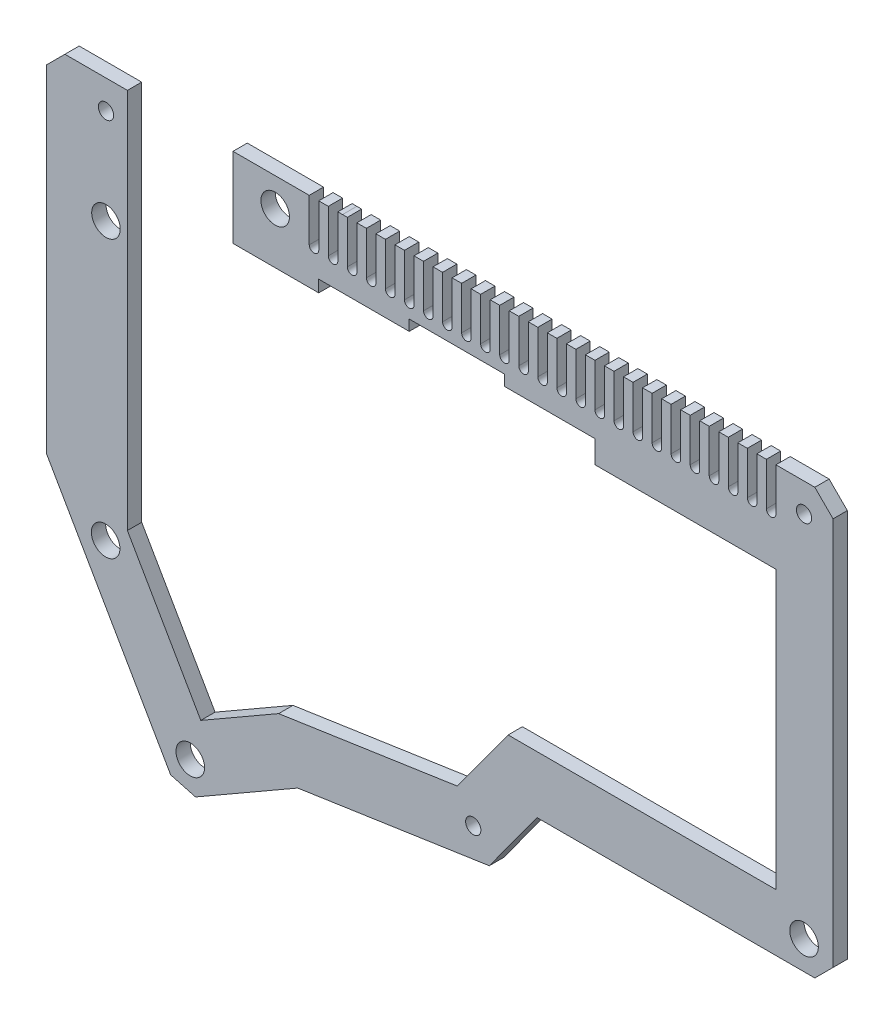
SolidWorks part; units mm, degrees
ref_plane "Plan de face" through (0, 0, 0) normal (0, 0, 1) x (1, 0, 0)
ref_plane "Plan de dessus" through (0, 0, 0) normal (0, 1, 0) x (1, 0, 0)
ref_plane "Plan de droite" through (0, 0, 0) normal (1, 0, 0) x (0, 0, -1)
sketch "Esquisse1" plane through (0, 0, 0) normal (0, 0, 1) x (1, 0, 0)
  line L0 (-117.3419, -15.4198) -> (-103.3409, -15.4198) construction
  line L1 (-103.3409, -15.4198) -> (-103.3409, -29.4208) construction
  line L2 (-103.3409, -29.4208) -> (-117.3419, -29.4208) construction
  line L3 (-117.3419, -29.4208) -> (-117.3419, -15.4198) construction
  line L4 (-98.3406, -27.0457) -> (-98.3406, -13.0447) construction
  line L5 (-98.3406, -13.0447) -> (-84.3396, -13.0447) construction
  line L6 (-84.3396, -13.0447) -> (-84.3396, -27.0457) construction
  line L7 (-84.3396, -27.0457) -> (-98.3406, -27.0457) construction
  line L8 (-79.3392, -24.6705) -> (-79.3392, -10.6695) construction
  line L9 (-79.3392, -10.6695) -> (-65.3382, -10.6695) construction
  line L10 (-65.3382, -10.6695) -> (-65.3382, -24.6705) construction
  line L11 (-65.3382, -24.6705) -> (-79.3392, -24.6705) construction
  line L12 (-60.3379, -27.0457) -> (-60.3379, -13.0447) construction
  line L13 (-60.3379, -13.0447) -> (-46.3369, -13.0447) construction
  line L14 (-46.3369, -13.0447) -> (-46.3369, -27.0457) construction
  line L15 (-46.3369, -27.0457) -> (-60.3379, -27.0457) construction
  line L16 (-41.3365, -31.796) -> (-41.3365, -17.795) construction
  line L17 (-41.3365, -17.795) -> (-27.3355, -17.795) construction
  line L18 (-27.3355, -17.795) -> (-27.3355, -31.796) construction
  line L19 (-27.3355, -31.796) -> (-41.3365, -31.796) construction
  line L20 (-22.3347, -31.796) -> (-22.3347, -17.795) construction
  line L21 (-22.3347, -17.795) -> (-8.3337, -17.795) construction
  line L22 (-8.3337, -17.795) -> (-8.3337, -31.796) construction
  line L23 (-8.3337, -31.796) -> (-22.3347, -31.796) construction
  line L24 (-117.3419, -34.4212) -> (-103.3409, -34.4212) construction
  line L25 (-103.3409, -34.4212) -> (-103.3409, -48.4222) construction
  line L26 (-103.3409, -48.4222) -> (-117.3419, -48.4222) construction
  line L27 (-117.3419, -48.4222) -> (-117.3419, -34.4212) construction
  line L28 (-98.3406, -32.046) -> (-84.3396, -32.046) construction
  line L29 (-84.3396, -32.046) -> (-84.3396, -46.047) construction
  line L30 (-84.3396, -46.047) -> (-98.3406, -46.047) construction
  line L31 (-98.3406, -46.047) -> (-98.3406, -32.046) construction
  line L32 (-79.3392, -29.6709) -> (-65.3382, -29.6709) construction
  line L33 (-65.3382, -29.6709) -> (-65.3382, -43.6718) construction
  line L34 (-65.3382, -43.6718) -> (-79.3392, -43.6718) construction
  line L35 (-79.3392, -43.6718) -> (-79.3392, -29.6709) construction
  line L36 (-60.3379, -32.046) -> (-46.3369, -32.046) construction
  line L37 (-46.3369, -32.046) -> (-46.3369, -46.047) construction
  line L38 (-46.3369, -46.047) -> (-60.3379, -46.047) construction
  line L39 (-60.3379, -46.047) -> (-60.3379, -32.046) construction
  line L40 (-41.3365, -36.7964) -> (-27.3355, -36.7964) construction
  line L41 (-27.3355, -36.7964) -> (-27.3355, -50.7973) construction
  line L42 (-27.3355, -50.7973) -> (-41.3365, -50.7973) construction
  line L43 (-41.3365, -50.7973) -> (-41.3365, -36.7964) construction
  line L44 (-22.3347, -36.7964) -> (-8.3337, -36.7964) construction
  line L45 (-8.3337, -36.7964) -> (-8.3337, -50.7973) construction
  line L46 (-8.3337, -50.7973) -> (-22.3347, -50.7973) construction
  line L47 (-22.3347, -50.7973) -> (-22.3347, -36.7964) construction
  line L48 (-22.3347, -55.7977) -> (-8.3337, -55.7977) construction
  line L49 (-8.3337, -55.7977) -> (-8.3337, -69.7987) construction
  line L50 (-8.3337, -69.7987) -> (-22.3347, -69.7987) construction
  line L51 (-22.3347, -69.7987) -> (-22.3347, -55.7977) construction
  line L52 (-41.3365, -55.7977) -> (-27.3355, -55.7977) construction
  line L53 (-27.3355, -55.7977) -> (-27.3355, -69.7987) construction
  line L54 (-27.3355, -69.7987) -> (-41.3365, -69.7987) construction
  line L55 (-41.3365, -69.7987) -> (-41.3365, -55.7977) construction
  line L56 (-60.3379, -51.0474) -> (-46.3369, -51.0474) construction
  line L57 (-46.3369, -51.0474) -> (-46.3369, -65.0484) construction
  line L58 (-46.3369, -65.0484) -> (-60.3379, -65.0484) construction
  line L59 (-60.3379, -65.0484) -> (-60.3379, -51.0474) construction
  line L60 (-79.3392, -48.6722) -> (-65.3382, -48.6722) construction
  line L61 (-65.3382, -48.6722) -> (-65.3382, -62.6732) construction
  line L62 (-65.3382, -62.6732) -> (-79.3392, -62.6732) construction
  line L63 (-79.3392, -62.6732) -> (-79.3392, -48.6722) construction
  line L64 (-98.3406, -51.0474) -> (-84.3396, -51.0474) construction
  line L65 (-84.3396, -51.0474) -> (-84.3396, -65.0484) construction
  line L66 (-84.3396, -65.0484) -> (-98.3406, -65.0484) construction
  line L67 (-98.3406, -65.0484) -> (-98.3406, -51.0474) construction
  line L68 (-117.3419, -53.4225) -> (-103.3409, -53.4225) construction
  line L69 (-103.3409, -53.4225) -> (-103.3409, -67.4235) construction
  line L70 (-103.3409, -67.4235) -> (-117.3419, -67.4235) construction
  line L71 (-117.3419, -67.4235) -> (-117.3419, -53.4225) construction
  line L72 (-88.8399, -70.6738) -> (-74.8389, -70.6738) construction
  line L73 (-74.8389, -70.6738) -> (-74.8389, -84.6747) construction
  line L74 (-74.8389, -84.6747) -> (-88.8399, -84.6747) construction
  line L75 (-88.8399, -84.6747) -> (-88.8399, -70.6738) construction
  line L76 (-111.4175, -75.4665) -> (-97.8899, -71.8565) construction
  line L77 (-97.8899, -71.8565) -> (-94.28, -85.3841) construction
  line L78 (-94.28, -85.3841) -> (-107.8075, -88.9941) construction
  line L79 (-107.8075, -88.9941) -> (-111.4175, -75.4665) construction
  line L80 (-134.6581, -81.5997) -> (-122.5281, -74.6075) construction
  line L81 (-122.5281, -74.6075) -> (-115.5359, -86.7375) construction
  line L82 (-115.5359, -86.7375) -> (-127.6659, -93.7297) construction
  line L83 (-127.6659, -93.7297) -> (-134.6581, -81.5997) construction
  line L86 (-6.3391, -71.9336) -> (-62.0853, -71.9336) construction
  line L89 (-72.824, -86.6446) -> (-62.0853, -71.9336) construction
  line L96 (-109.7697, -91.4639) -> (-73.0906, -86.6918) construction
  line L97 (-124.664, -99.8297) -> (-110.3971, -91.5881) construction
  line L98 (-139.9408, -76.5013) -> (-126.7151, -99.4281) construction
  line L99 (-119.8527, -15.5421) -> (-139.6028, -15.5421) construction
  line L100 (-100.8528, -13.2921) -> (-118.8527, -13.2921) construction
  line L101 (-63.8455, -8.5421) -> (-80.8528, -8.5421) construction
  line L102 (-44.8455, -10.792) -> (-62.8485, -10.792) construction
  line L103 (-25.8456, -15.5421) -> (-43.8486, -15.5421) construction
  line L104 (-6.8456, -15.5421) -> (-23.8529, -15.5421) construction
  line L105 (-6.2741, -71.3672) -> (-6.2741, -16.1136) construction
  line L106 (-23.8529, -71.9423) -> (-6.8456, -71.9423) construction
  line L107 (-61.8455, -71.9423) -> (-25.8456, -71.9423) construction
  line L108 (-72.6738, -86.4911) -> (-62.1363, -72.0583) construction
  line L109 (-140.1743, -16.1136) -> (-140.1743, -75.5958) construction
  line L110 (-134.3462, 1.5705) -> (-134.3466, -55.7217) construction
  line L111 (-134.3466, -55.7217) -> (-160.479, -70.8411) construction
  line L112 (-160.479, -70.8411) -> (-133.7613, -117.344) construction
  line L113 (-126.937, -119.1852) -> (-105.0783, -106.604) construction
  line L114 (-105.0783, -106.604) -> (-64.4097, -100.5586) construction
  line L115 (-64.4097, -100.5586) -> (-54.4636, -86.9336) construction
  line L116 (3.6609, -86.9336) -> (-54.4636, -86.9336) construction
  line L117 (8.6609, -81.9336) -> (8.6609, 1.315) construction
  line L122 (3.6609, 6.3153) -> (-96.3444, 6.3209) construction
  line L129 (8.6609, -86.9336) -> (8.6609, -0.6796) construction
  line L130 (-48.3431, 6.3182) -> (-96.3444, 6.3209) construction
  line L131 (-115.3458, 1.5705) -> (-134.3462, 1.5705) construction
  line L132 (-160.479, -3.4295) -> (-160.479, -70.8411) construction
  line L134 (-119.3463, 1.5705) -> (-119.3466, -64.3728) construction
  line L135 (-119.3466, -64.3728) -> (-135.695, -73.8315) construction
  line L136 (-140.0228, -71.3355) -> (-140.0228, 1.5705) construction
  line L138 (-160.479, -70.8411) -> (-131.2704, -121.6794) construction
  line L139 (-131.2704, -121.6794) -> (-105.0783, -106.604) construction
  line L140 (-133.7613, -117.344) -> (-126.937, -119.1852) construction
  line L142 (8.6609, 1.315) -> (3.6609, 6.3153) construction
  line L143 (8.6609, -86.9336) -> (-54.4636, -86.9336) construction
  line L144 (8.6609, -81.9336) -> (3.6609, -86.9336) construction
  line L147 (-103.3409, 6.3209) -> (-96.3444, 6.3209) construction
  line L148 (-103.3409, 6.3209) -> (-119.3463, 6.3209) construction
  line L149 (-119.3463, 6.3209) -> (-119.3463, 1.5705) construction
  line L150 (-140.0228, 1.5705) -> (-140.0228, 6.3209) construction
  line L151 (-140.0228, 6.3209) -> (-155.479, 6.3209) construction
  line L152 (-160.479, 1.3209) -> (-160.479, -3.4295) construction
  line L153 (-155.479, 6.3209) -> (-160.479, 1.3209) construction
  line L154 (8.6609, -1.685) -> (-119.3463, -1.6779) construction
  line L155 (-146.0924, -79.8227) -> (-128.3223, -110.752) construction
  line L156 (-128.3223, -110.752) -> (-107.7547, -98.9139) construction
  line L157 (-140.0228, -78.3428) -> (-126.1111, -102.5565)
  line L158 (-126.1111, -102.5565) -> (-109.762, -93.1464)
  line L159 (-109.762, -93.1464) -> (-72.2631, -87.5722)
  line L160 (-72.2631, -87.5722) -> (-61.5772, -72.9336)
  line L161 (-5.3391, -72.9336) -> (-61.5772, -72.9336)
  line L162 (-5.3391, -72.9336) -> (-5.3391, -14.6796)
  line L163 (-5.3391, -14.6796) -> (-43.3418, -14.6796)
  line L164 (-43.3418, -14.6796) -> (-43.3418, -9.9293)
  line L165 (-43.3418, -9.9293) -> (-62.3431, -9.9293)
  line L166 (-62.3431, -9.9293) -> (-62.3431, -7.681)
  line L167 (-62.3431, -7.681) -> (-82.3444, -7.6799)
  line L168 (-82.3444, -7.6799) -> (-82.3444, -9.9293)
  line L169 (-82.3444, -9.9293) -> (-101.3458, -9.9293)
  line L170 (-101.3458, -9.9293) -> (-101.3458, -12.4295)
  line L171 (-101.3458, -12.4295) -> (-119.3464, -12.4295)
  line L172 (-120.3463, -12.4295) -> (-120.3466, -64.3728) construction
  line L173 (-119.8474, -63.5072) -> (-140.5236, -75.4699) construction
  line L174 (-107.7547, -98.9139) -> (-68.8973, -93.1378) construction
  line L175 (-68.8973, -93.1378) -> (-58.5285, -78.9336) construction
  line L176 (0.6609, -78.9336) -> (-58.5285, -78.9336) construction
  line L177 (0.6609, -78.9336) -> (0.6609, -1.6845) construction
  line L178 (-62.3428, -1.681) -> (-82.3441, -1.6799) construction
  line L179 (0.6609, -78.9336) -> (0.6609, -14.6796) construction
  line L180 (-146.0228, -76.3355) -> (-146.0228, 1.5705) construction
  line L181 (-140.0228, -76.3355) -> (-140.0228, 1.5705) construction
  line L182 (-135.695, -73.8315) -> (-140.0228, -71.3355) construction
  line L183 (2.8324, 4.3153) -> (-96.3445, 4.3209)
  line L184 (-103.3409, 4.3209) -> (-96.3445, 4.3209)
  line L185 (-103.3409, 4.3209) -> (-119.3463, 4.3209)
  line L186 (-117.3463, 4.3209) -> (-117.3463, 1.5705) construction
  line L187 (-117.3463, 1.5705) -> (-117.3466, -65.5263) construction
  line L188 (-117.3466, -65.5263) -> (-135.6934, -76.1412) construction
  line L189 (-135.6934, -76.1412) -> (-142.0228, -72.4908) construction
  line L190 (-142.0228, -72.4908) -> (-142.0228, 1.5705) construction
  line L191 (-142.0228, 1.5705) -> (-142.0228, 4.3209) construction
  line L192 (-141.5228, 4.3209) -> (-154.6506, 4.3209)
  line L193 (-154.6506, 4.3209) -> (-158.479, 0.4924)
  line L194 (-158.479, 0.4924) -> (-158.479, -3.4295)
  line L195 (-158.479, -3.4295) -> (-158.479, -70.3075)
  line L196 (-158.479, -70.3075) -> (-132.44, -115.629)
  line L197 (-132.44, -115.629) -> (-127.2163, -117.0383)
  line L198 (-127.2163, -117.0383) -> (-105.7474, -104.6815)
  line L199 (-105.7474, -104.6815) -> (-65.5316, -98.7034)
  line L200 (-65.5316, -98.7034) -> (-55.4798, -84.9336)
  line L201 (2.8325, -84.9336) -> (-55.4798, -84.9336)
  line L202 (6.6609, -81.1052) -> (2.8325, -84.9336)
  line L203 (6.6609, -81.1052) -> (6.6609, 0.4866)
  line L204 (6.6609, 0.4866) -> (2.8324, 4.3153)
  line L205 (-103.3409, 4.3209) -> (-117.3463, 4.3209) construction
  line L206 (-142.0228, 4.3209) -> (-154.6506, 4.3209) construction
  line L207 (-140.0228, 4.3209) -> (-140.0228, -75.1802) construction
  line L208 (-119.3463, 4.3209) -> (-119.3464, -12.4295)
  line L209 (-140.0228, -78.3428) -> (-140.8899, -76.8336)
  line L210 (-101.3458, -12.4295) -> (-120.3463, -12.4295) construction
  line L211 (-140.8899, -76.8336) -> (-126.1111, -102.5565) construction
  line L217 (-6.3391, -71.9336) -> (-6.3391, -15.6796) construction
  line L220 (-6.3391, -15.6796) -> (-44.3418, -15.6796) construction
  line L221 (-44.3418, -15.6796) -> (-44.3418, -10.9293) construction
  line L222 (-44.3418, -10.9293) -> (-63.3431, -10.9293) construction
  line L223 (-63.3431, -10.9293) -> (-63.3431, -8.681) construction
  line L224 (-63.3431, -8.681) -> (-81.3444, -8.68) construction
  line L225 (-81.3444, -8.68) -> (-81.3444, -10.9293) construction
  line L226 (-81.3444, -10.9293) -> (-100.3458, -10.9293) construction
  line L227 (-100.3458, -10.9293) -> (-100.3458, -13.4295) construction
  line L228 (-100.3458, -13.4295) -> (-119.3463, -13.4295) construction
  line L231 (-119.3463, -13.4295) -> (-119.3466, -64.3728) construction
  line L232 (-119.3466, -64.3728) -> (-140.0228, -76.3355) construction
  line L233 (-140.0228, -76.3355) -> (-125.7426, -101.1906) construction
  line L234 (-125.7426, -101.1906) -> (-110.0965, -92.1851) construction
  line L235 (-110.0965, -92.1851) -> (-72.824, -86.6446) construction
  line L236 (-141.5228, -75.732) -> (-140.8899, -76.8336)
  line L238 (-141.5228, 4.3209) -> (-141.5228, -75.1802)
  line L239 (-141.5228, -75.1802) -> (-141.5228, -75.732)
  line L328 (-48.3431, 4.0707) -> (-48.3431, 6.3182) construction
  line L329 (-29.3418, 4.0707) -> (-48.3431, 4.0707) construction
  line L330 (-29.3418, -0.6796) -> (-29.3418, 4.0707) construction
  line L331 (8.6609, -0.6796) -> (-29.3418, -0.6796) construction
  line L332 (-115.3458, 4.0707) -> (-115.3458, 1.5705) construction
  line L333 (-96.3444, 4.0707) -> (-115.3458, 4.0707) construction
  line L334 (-96.3444, 6.3209) -> (-96.3444, 4.0707) construction
  circle A2 centre (0.6609, -1.6845) radius 1.6 construction
  circle A3 centre (0.6609, -1.6845) radius 3 construction
  circle A4 centre (-110.3971, -1.6784) radius 1.6 construction
  circle A5 centre (0.6609, -78.9336) radius 1.6 construction
  circle A6 centre (-68.8973, -93.1378) radius 1.6 construction
  circle A7 centre (-128.3223, -110.752) radius 1.6 construction
  circle A8 centre (-146.0924, -79.8227) radius 1.6 construction
  circle A9 centre (-146.0228, -1.6779) radius 1.6 construction
  point P138 (-160.479, 1.5705)
  point P139 (8.6609, 6.315)
  point P150 (-160.479, 6.3209)
  dimension "D3" = 3.2
  dimension "D4" = 6
  dimension "D6" = 3.2
  dimension "D7" = 3.2
  dimension "D8" = 3.2
  dimension "D9" = 3.2
  dimension "D10" = 3.2
  dimension "D15" = 3.2
  dimension "D2" = 6
  dimension "D1" = 15
  dimension "D5" = 1
  dimension "D13" = 6
  dimension "D16" = 2
  dimension "D17" = 1.5
extrude "Boss.-Extru.2" add sketch "Esquisse1" along normal blind 3
sketch "Esquisse2" plane through (0, 0, 3) normal (0, 0, 1) x (1, 0, 0)
  line L0 (6.6609, -3.0693) -> (-6.3391, -3.0693) construction
  line L1 (6.6609, -81.1052) -> (6.6609, 0.4866) construction
  line L2 (-6.3391, 4.3158) -> (-6.3391, -4.6842) construction
  line L3 (2.8324, 4.3153) -> (-96.3445, 4.3209) construction
  line L4 (-6.3391, 6.5821) -> (-6.3391, -4.6842) construction
  line L5 (-5.3391, 6.5821) -> (-5.3391, -4.6842)
  line L6 (-7.3391, 6.5821) -> (-7.3391, -4.6842)
  line L7 (-10.3391, 6.5821) -> (-10.3391, -4.6842) construction
  line L8 (-9.3391, 6.5821) -> (-9.3391, -4.6842)
  line L9 (-11.3391, 6.5821) -> (-11.3391, -4.6842)
  line L10 (-14.3391, 6.5821) -> (-14.3391, -4.6842) construction
  line L11 (-13.3391, 6.5821) -> (-13.3391, -4.6842)
  line L12 (-15.3391, 6.5821) -> (-15.3391, -4.6842)
  line L13 (-18.3391, 6.5821) -> (-18.3391, -4.6842) construction
  line L14 (-17.3391, 6.5821) -> (-17.3391, -4.6842)
  line L15 (-19.3391, 6.5821) -> (-19.3391, -4.6842)
  line L16 (-22.3391, 6.5821) -> (-22.3391, -4.6842) construction
  line L17 (-21.3391, 6.5821) -> (-21.3391, -4.6842)
  line L18 (-23.3391, 6.5821) -> (-23.3391, -4.6842)
  line L19 (-26.3391, 6.5821) -> (-26.3391, -4.6842) construction
  line L20 (-25.3391, 6.5821) -> (-25.3391, -4.6842)
  line L21 (-27.3391, 6.5821) -> (-27.3391, -4.6842)
  line L22 (-30.3391, 6.5821) -> (-30.3391, -4.6842) construction
  line L23 (-29.3391, 6.5821) -> (-29.3391, -4.6842)
  line L24 (-31.3391, 6.5821) -> (-31.3391, -4.6842)
  line L25 (-34.3391, 6.5821) -> (-34.3391, -4.6842) construction
  line L26 (-33.3391, 6.5821) -> (-33.3391, -4.6842)
  line L27 (-35.3391, 6.5821) -> (-35.3391, -4.6842)
  line L28 (-38.3391, 6.5821) -> (-38.3391, -4.6842) construction
  line L29 (-37.3391, 6.5821) -> (-37.3391, -4.6842)
  line L30 (-39.3391, 6.5821) -> (-39.3391, -4.6842)
  line L31 (-42.3391, 6.5821) -> (-42.3391, -4.6842) construction
  line L32 (-41.3391, 6.5821) -> (-41.3391, -4.6842)
  line L33 (-43.3391, 6.5821) -> (-43.3391, -4.6842)
  line L34 (-46.3391, 6.5821) -> (-46.3391, -4.6842) construction
  line L35 (-45.3391, 6.5821) -> (-45.3391, -4.6842)
  line L36 (-47.3391, 6.5821) -> (-47.3391, -4.6842)
  line L37 (-50.3391, 6.5821) -> (-50.3391, -4.6842) construction
  line L38 (-49.3391, 6.5821) -> (-49.3391, -4.6842)
  line L39 (-51.3391, 6.5821) -> (-51.3391, -4.6842)
  line L40 (-54.3391, 6.5821) -> (-54.3391, -4.6842) construction
  line L41 (-53.3391, 6.5821) -> (-53.3391, -4.6842)
  line L42 (-55.3391, 6.5821) -> (-55.3391, -4.6842)
  line L43 (-58.3391, 6.5821) -> (-58.3391, -4.6842) construction
  line L44 (-57.3391, 6.5821) -> (-57.3391, -4.6842)
  line L45 (-59.3391, 6.5821) -> (-59.3391, -4.6842)
  line L46 (-62.3391, 6.5821) -> (-62.3391, -4.6842) construction
  line L47 (-61.3391, 6.5821) -> (-61.3391, -4.6842)
  line L48 (-63.3391, 6.5821) -> (-63.3391, -4.6842)
  line L49 (-66.3391, 6.5821) -> (-66.3391, -4.6842) construction
  line L50 (-65.3391, 6.5821) -> (-65.3391, -4.6842)
  line L51 (-67.3391, 6.5821) -> (-67.3391, -4.6842)
  line L52 (-70.3391, 6.5821) -> (-70.3391, -4.6842) construction
  line L53 (-69.3391, 6.5821) -> (-69.3391, -4.6842)
  line L54 (-71.3391, 6.5821) -> (-71.3391, -4.6842)
  line L55 (-74.3391, 6.5821) -> (-74.3391, -4.6842) construction
  line L56 (-73.3391, 6.5821) -> (-73.3391, -4.6842)
  line L57 (-75.3391, 6.5821) -> (-75.3391, -4.6842)
  line L58 (-78.3391, 6.5821) -> (-78.3391, -4.6842) construction
  line L59 (-77.3391, 6.5821) -> (-77.3391, -4.6842)
  line L60 (-79.3391, 6.5821) -> (-79.3391, -4.6842)
  line L61 (-82.3391, 6.5821) -> (-82.3391, -4.6842) construction
  line L62 (-81.3391, 6.5821) -> (-81.3391, -4.6842)
  line L63 (-83.3391, 6.5821) -> (-83.3391, -4.6842)
  line L64 (-86.3391, 6.5821) -> (-86.3391, -4.6842) construction
  line L65 (-85.3391, 6.5821) -> (-85.3391, -4.6842)
  line L66 (-87.3391, 6.5821) -> (-87.3391, -4.6842)
  line L67 (-90.3391, 6.5821) -> (-90.3391, -4.6842) construction
  line L68 (-89.3391, 6.5821) -> (-89.3391, -4.6842)
  line L69 (-91.3391, 6.5821) -> (-91.3391, -4.6842)
  line L70 (-94.3391, 6.5821) -> (-94.3391, -4.6842) construction
  line L71 (-93.3391, 6.5821) -> (-93.3391, -4.6842)
  line L72 (-95.3391, 6.5821) -> (-95.3391, -4.6842)
  line L73 (-98.3391, 6.5821) -> (-98.3391, -4.6842) construction
  line L74 (-97.3391, 6.5821) -> (-97.3391, -4.6842)
  line L75 (-99.3391, 6.5821) -> (-99.3391, -4.6842)
  line L76 (-102.3391, 6.5821) -> (-102.3391, -4.6842) construction
  line L77 (-101.3391, 6.5821) -> (-101.3391, -4.6842)
  line L78 (-103.3391, 6.5821) -> (-103.3391, -4.6842)
  arc A0 (-5.3391, 6.5821) -> (-7.3391, 6.5821) centre (-6.3391, 6.5821) ccw
  arc A1 (-7.3391, -4.6842) -> (-5.3391, -4.6842) centre (-6.3391, -4.6842) ccw
  arc A2 (-9.3391, 6.5821) -> (-11.3391, 6.5821) centre (-10.3391, 6.5821) ccw
  arc A3 (-11.3391, -4.6842) -> (-9.3391, -4.6842) centre (-10.3391, -4.6842) ccw
  arc A4 (-13.3391, 6.5821) -> (-15.3391, 6.5821) centre (-14.3391, 6.5821) ccw
  arc A5 (-15.3391, -4.6842) -> (-13.3391, -4.6842) centre (-14.3391, -4.6842) ccw
  arc A6 (-17.3391, 6.5821) -> (-19.3391, 6.5821) centre (-18.3391, 6.5821) ccw
  arc A7 (-19.3391, -4.6842) -> (-17.3391, -4.6842) centre (-18.3391, -4.6842) ccw
  arc A8 (-21.3391, 6.5821) -> (-23.3391, 6.5821) centre (-22.3391, 6.5821) ccw
  arc A9 (-23.3391, -4.6842) -> (-21.3391, -4.6842) centre (-22.3391, -4.6842) ccw
  arc A10 (-25.3391, 6.5821) -> (-27.3391, 6.5821) centre (-26.3391, 6.5821) ccw
  arc A11 (-27.3391, -4.6842) -> (-25.3391, -4.6842) centre (-26.3391, -4.6842) ccw
  arc A12 (-29.3391, 6.5821) -> (-31.3391, 6.5821) centre (-30.3391, 6.5821) ccw
  arc A13 (-31.3391, -4.6842) -> (-29.3391, -4.6842) centre (-30.3391, -4.6842) ccw
  arc A14 (-33.3391, 6.5821) -> (-35.3391, 6.5821) centre (-34.3391, 6.5821) ccw
  arc A15 (-35.3391, -4.6842) -> (-33.3391, -4.6842) centre (-34.3391, -4.6842) ccw
  arc A16 (-37.3391, 6.5821) -> (-39.3391, 6.5821) centre (-38.3391, 6.5821) ccw
  arc A17 (-39.3391, -4.6842) -> (-37.3391, -4.6842) centre (-38.3391, -4.6842) ccw
  arc A18 (-41.3391, 6.5821) -> (-43.3391, 6.5821) centre (-42.3391, 6.5821) ccw
  arc A19 (-43.3391, -4.6842) -> (-41.3391, -4.6842) centre (-42.3391, -4.6842) ccw
  arc A20 (-45.3391, 6.5821) -> (-47.3391, 6.5821) centre (-46.3391, 6.5821) ccw
  arc A21 (-47.3391, -4.6842) -> (-45.3391, -4.6842) centre (-46.3391, -4.6842) ccw
  arc A22 (-49.3391, 6.5821) -> (-51.3391, 6.5821) centre (-50.3391, 6.5821) ccw
  arc A23 (-51.3391, -4.6842) -> (-49.3391, -4.6842) centre (-50.3391, -4.6842) ccw
  arc A24 (-53.3391, 6.5821) -> (-55.3391, 6.5821) centre (-54.3391, 6.5821) ccw
  arc A25 (-55.3391, -4.6842) -> (-53.3391, -4.6842) centre (-54.3391, -4.6842) ccw
  arc A26 (-57.3391, 6.5821) -> (-59.3391, 6.5821) centre (-58.3391, 6.5821) ccw
  arc A27 (-59.3391, -4.6842) -> (-57.3391, -4.6842) centre (-58.3391, -4.6842) ccw
  arc A28 (-61.3391, 6.5821) -> (-63.3391, 6.5821) centre (-62.3391, 6.5821) ccw
  arc A29 (-63.3391, -4.6842) -> (-61.3391, -4.6842) centre (-62.3391, -4.6842) ccw
  arc A30 (-65.3391, 6.5821) -> (-67.3391, 6.5821) centre (-66.3391, 6.5821) ccw
  arc A31 (-67.3391, -4.6842) -> (-65.3391, -4.6842) centre (-66.3391, -4.6842) ccw
  arc A32 (-69.3391, 6.5821) -> (-71.3391, 6.5821) centre (-70.3391, 6.5821) ccw
  arc A33 (-71.3391, -4.6842) -> (-69.3391, -4.6842) centre (-70.3391, -4.6842) ccw
  arc A34 (-73.3391, 6.5821) -> (-75.3391, 6.5821) centre (-74.3391, 6.5821) ccw
  arc A35 (-75.3391, -4.6842) -> (-73.3391, -4.6842) centre (-74.3391, -4.6842) ccw
  arc A36 (-77.3391, 6.5821) -> (-79.3391, 6.5821) centre (-78.3391, 6.5821) ccw
  arc A37 (-79.3391, -4.6842) -> (-77.3391, -4.6842) centre (-78.3391, -4.6842) ccw
  arc A38 (-81.3391, 6.5821) -> (-83.3391, 6.5821) centre (-82.3391, 6.5821) ccw
  arc A39 (-83.3391, -4.6842) -> (-81.3391, -4.6842) centre (-82.3391, -4.6842) ccw
  arc A40 (-85.3391, 6.5821) -> (-87.3391, 6.5821) centre (-86.3391, 6.5821) ccw
  arc A41 (-87.3391, -4.6842) -> (-85.3391, -4.6842) centre (-86.3391, -4.6842) ccw
  arc A42 (-89.3391, 6.5821) -> (-91.3391, 6.5821) centre (-90.3391, 6.5821) ccw
  arc A43 (-91.3391, -4.6842) -> (-89.3391, -4.6842) centre (-90.3391, -4.6842) ccw
  arc A44 (-93.3391, 6.5821) -> (-95.3391, 6.5821) centre (-94.3391, 6.5821) ccw
  arc A45 (-95.3391, -4.6842) -> (-93.3391, -4.6842) centre (-94.3391, -4.6842) ccw
  arc A46 (-97.3391, 6.5821) -> (-99.3391, 6.5821) centre (-98.3391, 6.5821) ccw
  arc A47 (-99.3391, -4.6842) -> (-97.3391, -4.6842) centre (-98.3391, -4.6842) ccw
  arc A48 (-101.3391, 6.5821) -> (-103.3391, 6.5821) centre (-102.3391, 6.5821) ccw
  arc A49 (-103.3391, -4.6842) -> (-101.3391, -4.6842) centre (-102.3391, -4.6842) ccw
  point P9 (-6.3391, 0.949)
  point P17 (-10.3391, 0.949)
  point P24 (-14.3391, 0.949)
  point P31 (-18.3391, 0.949)
  point P38 (-22.3391, 0.949)
  point P45 (-26.3391, 0.949)
  point P52 (-30.3391, 0.949)
  point P59 (-34.3391, 0.949)
  point P66 (-38.3391, 0.949)
  point P73 (-42.3391, 0.949)
  point P80 (-46.3391, 0.949)
  point P87 (-50.3391, 0.949)
  point P94 (-54.3391, 0.949)
  point P101 (-58.3391, 0.949)
  point P108 (-62.3391, 0.949)
  point P115 (-66.3391, 0.949)
  point P122 (-70.3391, 0.949)
  point P129 (-74.3391, 0.949)
  point P136 (-78.3391, 0.949)
  point P143 (-82.3391, 0.949)
  point P150 (-86.3391, 0.949)
  point P157 (-90.3391, 0.949)
  point P164 (-94.3391, 0.949)
  point P171 (-98.3391, 0.949)
  point P178 (-102.3391, 0.949)
  dimension "D3" = 25
  dimension "D1" = 13
  dimension "D2" = 9
extrude "Enlèv. mat.-Extru.1" cut sketch "Esquisse2" against normal blind 3
sketch "Esquisse3" plane through (0, 0, 0) normal (0, 0, 1) x (1, 0, 0)
  line L96 (-146.0228, -1.6779) -> (-146.0228, -21.6779) construction
  circle A3 centre (0.5703, -1.6845) radius 3 construction
  circle A10 centre (-110.4876, -1.6784) radius 3
  circle A11 centre (-146.0228, -1.6779) radius 3 construction
  circle A12 centre (-146.0924, -79.8227) radius 3
  circle A13 centre (-128.3223, -110.752) radius 3
  circle A14 centre (-68.8973, -93.1378) radius 3 construction
  circle A15 centre (0.5703, -78.9336) radius 3
  circle A16 centre (-68.8973, -93.1378) radius 1.6
  circle A17 centre (-146.0228, -1.6779) radius 1.6
  circle A18 centre (0.5703, -1.6845) radius 1.6
  circle A19 centre (-146.0228, -21.6779) radius 3
  point P89 (-119.3466, -64.3728)
  point P133 (-96.435, 6.3209)
  point P137 (-119.3463, 1.5705)
  point P145 (3.5703, 6.3153)
  point P152 (-119.3463, 6.3209)
  point P158 (-140.8899, -76.8336)
  point P161 (-126.1111, -102.5565)
  point P174 (-101.3458, -12.4295)
  point P175 (-120.3463, -12.4295)
  point P199 (3.1561, 5.3153)
  point P200 (-96.435, 5.3209)
  point P201 (-103.4315, 5.3209)
  dimension "D3" = 3.2
  dimension "D4" = 6
  dimension "D1" = 3.2
  dimension "D2" = 3.2
extrude "Enlèv. mat.-Extru.3" cut sketch "Esquisse3" along normal blind 10
sketch "Esquisse4" plane through (0, 0, 3) normal (0, 0, 1) x (1, 0, 0)
  line L106 (2.8324, 4.3153) -> (-5.3391, 4.3158)
  line L107 (-5.3391, 4.3158) -> (-5.3391, -4.6842)
  line L108 (-7.3391, -4.6842) -> (-7.3391, 4.3159)
  line L109 (-7.3391, 4.3159) -> (-9.3391, 4.316)
  line L110 (-9.3391, 4.316) -> (-9.3391, -4.6842)
  line L111 (-11.3391, -4.6842) -> (-11.3391, 4.3161)
  line L112 (-11.3391, 4.3161) -> (-13.3391, 4.3162)
  line L113 (-13.3391, 4.3162) -> (-13.3391, -4.6842)
  line L114 (-15.3391, -4.6842) -> (-15.3391, 4.3163)
  line L115 (-15.3391, 4.3163) -> (-17.3391, 4.3165)
  line L116 (-17.3391, 4.3165) -> (-17.3391, -4.6842)
  line L117 (-19.3391, -4.6842) -> (-19.3391, 4.3166)
  line L118 (-19.3391, 4.3166) -> (-21.3391, 4.3167)
  line L119 (-21.3391, 4.3167) -> (-21.3391, -4.6842)
  line L120 (-23.3391, -4.6842) -> (-23.3391, 4.3168)
  line L121 (-23.3391, 4.3168) -> (-25.3391, 4.3169)
  line L122 (-25.3391, 4.3169) -> (-25.3391, -4.6842)
  line L123 (-27.3391, -4.6842) -> (-27.3391, 4.317)
  line L124 (-27.3391, 4.317) -> (-29.3391, 4.3171)
  line L125 (-29.3391, 4.3171) -> (-29.3391, -4.6842)
  line L126 (-31.3391, -4.6842) -> (-31.3391, 4.3172)
  line L127 (-31.3391, 4.3172) -> (-33.3391, 4.3173)
  line L128 (-33.3391, 4.3173) -> (-33.3391, -4.6842)
  line L129 (-35.3391, -4.6842) -> (-35.3391, 4.3175)
  line L130 (-35.3391, 4.3175) -> (-37.3391, 4.3176)
  line L131 (-37.3391, 4.3176) -> (-37.3391, -4.6842)
  line L132 (-39.3391, -4.6842) -> (-39.3391, 4.3177)
  line L133 (-39.3391, 4.3177) -> (-41.3391, 4.3178)
  line L134 (-41.3391, 4.3178) -> (-41.3391, -4.6842)
  line L135 (-43.3391, -4.6842) -> (-43.3391, 4.3179)
  line L136 (-43.3391, 4.3179) -> (-45.3391, 4.318)
  line L137 (-45.3391, 4.318) -> (-45.3391, -4.6842)
  line L138 (-47.3391, -4.6842) -> (-47.3391, 4.3181)
  line L139 (-47.3391, 4.3181) -> (-49.3391, 4.3182)
  line L140 (-49.3391, 4.3182) -> (-49.3391, -4.6842)
  line L141 (-51.3391, -4.6842) -> (-51.3391, 4.3183)
  line L142 (-51.3391, 4.3183) -> (-53.3391, 4.3185)
  line L143 (-53.3391, 4.3185) -> (-53.3391, -4.6842)
  line L144 (-55.3391, -4.6842) -> (-55.3391, 4.3186)
  line L145 (-55.3391, 4.3186) -> (-57.3391, 4.3187)
  line L146 (-57.3391, 4.3187) -> (-57.3391, -4.6842)
  line L147 (-59.3391, -4.6842) -> (-59.3391, 4.3188)
  line L148 (-59.3391, 4.3188) -> (-61.3391, 4.3189)
  line L149 (-61.3391, 4.3189) -> (-61.3391, -4.6842)
  line L150 (-63.3391, -4.6842) -> (-63.3391, 4.319)
  line L151 (-63.3391, 4.319) -> (-65.3391, 4.3191)
  line L152 (-65.3391, 4.3191) -> (-65.3391, -4.6842)
  line L153 (-67.3391, -4.6842) -> (-67.3391, 4.3192)
  line L154 (-67.3391, 4.3192) -> (-69.3391, 4.3194)
  line L155 (-69.3391, 4.3194) -> (-69.3391, -4.6842)
  line L156 (-71.3391, -4.6842) -> (-71.3391, 4.3195)
  line L157 (-71.3391, 4.3195) -> (-73.3391, 4.3196)
  line L158 (-73.3391, 4.3196) -> (-73.3391, -4.6842)
  line L159 (-75.3391, -4.6842) -> (-75.3391, 4.3197)
  line L160 (-75.3391, 4.3197) -> (-77.3391, 4.3198)
  line L161 (-77.3391, 4.3198) -> (-77.3391, -4.6842)
  line L162 (-79.3391, -4.6842) -> (-79.3391, 4.3199)
  line L163 (-79.3391, 4.3199) -> (-81.3391, 4.32)
  line L164 (-81.3391, 4.32) -> (-81.3391, -4.6842)
  line L165 (-83.3391, -4.6842) -> (-83.3391, 4.3201)
  line L166 (-83.3391, 4.3201) -> (-85.3391, 4.3202)
  line L167 (-85.3391, 4.3202) -> (-85.3391, -4.6842)
  line L168 (-87.3391, -4.6842) -> (-87.3391, 4.3204)
  line L169 (-87.3391, 4.3204) -> (-89.3391, 4.3205)
  line L170 (-89.3391, 4.3205) -> (-89.3391, -4.6842)
  line L171 (-91.3391, -4.6842) -> (-91.3391, 4.3206)
  line L172 (-91.3391, 4.3206) -> (-93.3391, 4.3207)
  line L173 (-93.3391, 4.3207) -> (-93.3391, -4.6842)
  line L174 (-95.3391, -4.6842) -> (-95.3391, 4.3208)
  line L175 (-95.3391, 4.3208) -> (-96.3445, 4.3209)
  line L176 (-96.3445, 4.3209) -> (-97.3391, 4.3209)
  line L177 (-97.3391, 4.3209) -> (-97.3391, -4.6842)
  line L178 (-99.3391, -4.6842) -> (-99.3391, 4.3209)
  line L179 (-99.3391, 4.3209) -> (-101.3391, 4.3209)
  line L180 (-101.3391, 4.3209) -> (-101.3391, -4.6842)
  line L181 (-103.3391, -4.6842) -> (-103.3391, 4.3209)
  line L182 (-103.3391, 4.3209) -> (-119.3463, 4.3209)
  line L183 (-119.3463, 4.3209) -> (-119.3464, -12.4295)
  line L184 (-119.3464, -12.4295) -> (-101.3458, -12.4295)
  line L185 (-101.3458, -12.4295) -> (-101.3458, -9.9293)
  line L186 (-101.3458, -9.9293) -> (-82.3444, -9.9293)
  line L187 (-82.3444, -9.9293) -> (-82.3444, -7.6799)
  line L188 (-82.3444, -7.6799) -> (-62.3431, -7.681)
  line L189 (-62.3431, -7.681) -> (-62.3431, -9.9293)
  line L190 (-62.3431, -9.9293) -> (-43.3418, -9.9293)
  line L191 (-43.3418, -9.9293) -> (-43.3418, -14.6796)
  line L192 (-43.3418, -14.6796) -> (-5.3391, -14.6796)
  line L193 (-5.3391, -14.6796) -> (-5.3391, -72.9336)
  line L194 (-5.3391, -72.9336) -> (-61.5772, -72.9336)
  line L195 (-61.5772, -72.9336) -> (-72.2631, -87.5722)
  line L196 (-72.2631, -87.5722) -> (-109.762, -93.1464)
  line L197 (-109.762, -93.1464) -> (-126.1111, -102.5565)
  line L198 (-126.1111, -102.5565) -> (-141.5228, -75.732)
  line L199 (-141.5228, -75.732) -> (-141.5228, 4.3209)
  line L200 (-141.5228, 4.3209) -> (-154.6506, 4.3209)
  line L201 (-154.6506, 4.3209) -> (-158.479, 0.4924)
  line L202 (-158.479, 0.4924) -> (-158.479, -70.3075)
  line L203 (-158.479, -70.3075) -> (-132.44, -115.629)
  line L204 (-132.44, -115.629) -> (-127.2163, -117.0383)
  line L205 (-127.2163, -117.0383) -> (-105.7474, -104.6815)
  line L206 (-105.7474, -104.6815) -> (-65.5316, -98.7034)
  line L207 (-65.5316, -98.7034) -> (-55.4798, -84.9336)
  line L208 (-55.4798, -84.9336) -> (2.8325, -84.9336)
  line L209 (2.8325, -84.9336) -> (6.6609, -81.1052)
  line L210 (6.6609, -81.1052) -> (6.6609, 0.4866)
  line L211 (6.6609, 0.4866) -> (2.8324, 4.3153)
  line L212 (2.8324, 4.3153) -> (-5.3391, 4.3158)
  line L213 (-5.3391, 4.3158) -> (-5.3391, -4.6842)
  line L214 (-7.3391, -4.6842) -> (-7.3391, 4.3159)
  line L215 (-7.3391, 4.3159) -> (-9.3391, 4.316)
  line L216 (-9.3391, 4.316) -> (-9.3391, -4.6842)
  line L217 (-11.3391, -4.6842) -> (-11.3391, 4.3161)
  line L218 (-11.3391, 4.3161) -> (-13.3391, 4.3162)
  line L219 (-13.3391, 4.3162) -> (-13.3391, -4.6842)
  line L220 (-15.3391, -4.6842) -> (-15.3391, 4.3163)
  line L221 (-15.3391, 4.3163) -> (-17.3391, 4.3165)
  line L222 (-17.3391, 4.3165) -> (-17.3391, -4.6842)
  line L223 (-19.3391, -4.6842) -> (-19.3391, 4.3166)
  line L224 (-19.3391, 4.3166) -> (-21.3391, 4.3167)
  line L225 (-21.3391, 4.3167) -> (-21.3391, -4.6842)
  line L226 (-23.3391, -4.6842) -> (-23.3391, 4.3168)
  line L227 (-23.3391, 4.3168) -> (-25.3391, 4.3169)
  line L228 (-25.3391, 4.3169) -> (-25.3391, -4.6842)
  line L229 (-27.3391, -4.6842) -> (-27.3391, 4.317)
  line L230 (-27.3391, 4.317) -> (-29.3391, 4.3171)
  line L231 (-29.3391, 4.3171) -> (-29.3391, -4.6842)
  line L232 (-31.3391, -4.6842) -> (-31.3391, 4.3172)
  line L233 (-31.3391, 4.3172) -> (-33.3391, 4.3173)
  line L234 (-33.3391, 4.3173) -> (-33.3391, -4.6842)
  line L235 (-35.3391, -4.6842) -> (-35.3391, 4.3175)
  line L236 (-35.3391, 4.3175) -> (-37.3391, 4.3176)
  line L237 (-37.3391, 4.3176) -> (-37.3391, -4.6842)
  line L238 (-39.3391, -4.6842) -> (-39.3391, 4.3177)
  line L239 (-39.3391, 4.3177) -> (-41.3391, 4.3178)
  line L240 (-41.3391, 4.3178) -> (-41.3391, -4.6842)
  line L241 (-43.3391, -4.6842) -> (-43.3391, 4.3179)
  line L242 (-43.3391, 4.3179) -> (-45.3391, 4.318)
  line L243 (-45.3391, 4.318) -> (-45.3391, -4.6842)
  line L244 (-47.3391, -4.6842) -> (-47.3391, 4.3181)
  line L245 (-47.3391, 4.3181) -> (-49.3391, 4.3182)
  line L246 (-49.3391, 4.3182) -> (-49.3391, -4.6842)
  line L247 (-51.3391, -4.6842) -> (-51.3391, 4.3183)
  line L248 (-51.3391, 4.3183) -> (-53.3391, 4.3185)
  line L249 (-53.3391, 4.3185) -> (-53.3391, -4.6842)
  line L250 (-55.3391, -4.6842) -> (-55.3391, 4.3186)
  line L251 (-55.3391, 4.3186) -> (-57.3391, 4.3187)
  line L252 (-57.3391, 4.3187) -> (-57.3391, -4.6842)
  line L253 (-59.3391, -4.6842) -> (-59.3391, 4.3188)
  line L254 (-59.3391, 4.3188) -> (-61.3391, 4.3189)
  line L255 (-61.3391, 4.3189) -> (-61.3391, -4.6842)
  line L256 (-63.3391, -4.6842) -> (-63.3391, 4.319)
  line L257 (-63.3391, 4.319) -> (-65.3391, 4.3191)
  line L258 (-65.3391, 4.3191) -> (-65.3391, -4.6842)
  line L259 (-67.3391, -4.6842) -> (-67.3391, 4.3192)
  line L260 (-67.3391, 4.3192) -> (-69.3391, 4.3194)
  line L261 (-69.3391, 4.3194) -> (-69.3391, -4.6842)
  line L262 (-71.3391, -4.6842) -> (-71.3391, 4.3195)
  line L263 (-71.3391, 4.3195) -> (-73.3391, 4.3196)
  line L264 (-73.3391, 4.3196) -> (-73.3391, -4.6842)
  line L265 (-75.3391, -4.6842) -> (-75.3391, 4.3197)
  line L266 (-75.3391, 4.3197) -> (-77.3391, 4.3198)
  line L267 (-77.3391, 4.3198) -> (-77.3391, -4.6842)
  line L268 (-79.3391, -4.6842) -> (-79.3391, 4.3199)
  line L269 (-79.3391, 4.3199) -> (-81.3391, 4.32)
  line L270 (-81.3391, 4.32) -> (-81.3391, -4.6842)
  line L271 (-83.3391, -4.6842) -> (-83.3391, 4.3201)
  line L272 (-83.3391, 4.3201) -> (-85.3391, 4.3202)
  line L273 (-85.3391, 4.3202) -> (-85.3391, -4.6842)
  line L274 (-87.3391, -4.6842) -> (-87.3391, 4.3204)
  line L275 (-87.3391, 4.3204) -> (-89.3391, 4.3205)
  line L276 (-89.3391, 4.3205) -> (-89.3391, -4.6842)
  line L277 (-91.3391, -4.6842) -> (-91.3391, 4.3206)
  line L278 (-91.3391, 4.3206) -> (-93.3391, 4.3207)
  line L279 (-93.3391, 4.3207) -> (-93.3391, -4.6842)
  line L280 (-95.3391, -4.6842) -> (-95.3391, 4.3208)
  line L281 (-95.3391, 4.3208) -> (-96.3445, 4.3209)
  line L282 (-96.3445, 4.3209) -> (-97.3391, 4.3209)
  line L283 (-97.3391, 4.3209) -> (-97.3391, -4.6842)
  line L284 (-99.3391, -4.6842) -> (-99.3391, 4.3209)
  line L285 (-99.3391, 4.3209) -> (-101.3391, 4.3209)
  line L286 (-101.3391, 4.3209) -> (-101.3391, -4.6842)
  line L287 (-103.3391, -4.6842) -> (-103.3391, 4.3209)
  line L288 (-103.3391, 4.3209) -> (-119.3463, 4.3209)
  line L289 (-119.3463, 4.3209) -> (-119.3464, -12.4295)
  line L290 (-119.3464, -12.4295) -> (-101.3458, -12.4295)
  line L291 (-101.3458, -12.4295) -> (-101.3458, -9.9293)
  line L292 (-101.3458, -9.9293) -> (-82.3444, -9.9293)
  line L293 (-82.3444, -9.9293) -> (-82.3444, -7.6799)
  line L294 (-82.3444, -7.6799) -> (-62.3431, -7.681)
  line L295 (-62.3431, -7.681) -> (-62.3431, -9.9293)
  line L296 (-62.3431, -9.9293) -> (-43.3418, -9.9293)
  line L297 (-43.3418, -9.9293) -> (-43.3418, -14.6796)
  line L298 (-43.3418, -14.6796) -> (-5.3391, -14.6796)
  line L299 (-5.3391, -14.6796) -> (-5.3391, -72.9336)
  line L300 (-5.3391, -72.9336) -> (-61.5772, -72.9336)
  line L301 (-61.5772, -72.9336) -> (-72.2631, -87.5722)
  line L302 (-72.2631, -87.5722) -> (-109.762, -93.1464)
  line L303 (-109.762, -93.1464) -> (-126.1111, -102.5565)
  line L304 (-126.1111, -102.5565) -> (-141.5228, -75.732)
  line L305 (-141.5228, -75.732) -> (-141.5228, 4.3209)
  line L306 (-141.5228, 4.3209) -> (-154.6506, 4.3209)
  line L307 (-154.6506, 4.3209) -> (-158.479, 0.4924)
  line L308 (-158.479, 0.4924) -> (-158.479, -70.3075)
  line L309 (-158.479, -70.3075) -> (-132.44, -115.629)
  line L310 (-132.44, -115.629) -> (-127.2163, -117.0383)
  line L311 (-127.2163, -117.0383) -> (-105.7474, -104.6815)
  line L312 (-105.7474, -104.6815) -> (-65.5316, -98.7034)
  line L313 (-65.5316, -98.7034) -> (-55.4798, -84.9336)
  line L314 (-55.4798, -84.9336) -> (2.8325, -84.9336)
  line L315 (2.8325, -84.9336) -> (6.6609, -81.1052)
  line L316 (6.6609, -81.1052) -> (6.6609, 0.4866)
  line L317 (6.6609, 0.4866) -> (2.8324, 4.3153)
  circle A0 centre (-146.0228, -1.6779) radius 1.6 construction
  circle A1 centre (-146.0228, -21.6779) radius 3 construction
  circle A2 centre (-146.0924, -79.8227) radius 3 construction
  circle A3 centre (-128.3223, -110.752) radius 3 construction
  circle A4 centre (-68.8973, -93.1378) radius 1.6 construction
  circle A5 centre (-110.4876, -1.6784) radius 3 construction
  circle A6 centre (0.5703, -1.6845) radius 1.6 construction
  circle A7 centre (0.5703, -78.9336) radius 3 construction
  circle A8 centre (-146.0228, -1.6779) radius 1.6
  circle A9 centre (-146.0228, -21.6779) radius 3
  circle A10 centre (-146.0924, -79.8227) radius 3
  circle A11 centre (-128.3223, -110.752) radius 3
  circle A12 centre (-68.8973, -93.1378) radius 1.6
  circle A13 centre (-110.4876, -1.6784) radius 3
  circle A14 centre (0.5703, -1.6845) radius 1.6
  circle A15 centre (0.5703, -78.9336) radius 3
  arc A25 (-7.3391, -4.6842) -> (-5.3391, -4.6842) centre (-6.3391, -4.6842) ccw
  arc A26 (-11.3391, -4.6842) -> (-9.3391, -4.6842) centre (-10.3391, -4.6842) ccw
  arc A27 (-15.3391, -4.6842) -> (-13.3391, -4.6842) centre (-14.3391, -4.6842) ccw
  arc A28 (-19.3391, -4.6842) -> (-17.3391, -4.6842) centre (-18.3391, -4.6842) ccw
  arc A29 (-23.3391, -4.6842) -> (-21.3391, -4.6842) centre (-22.3391, -4.6842) ccw
  arc A30 (-27.3391, -4.6842) -> (-25.3391, -4.6842) centre (-26.3391, -4.6842) ccw
  arc A31 (-31.3391, -4.6842) -> (-29.3391, -4.6842) centre (-30.3391, -4.6842) ccw
  arc A32 (-35.3391, -4.6842) -> (-33.3391, -4.6842) centre (-34.3391, -4.6842) ccw
  arc A33 (-39.3391, -4.6842) -> (-37.3391, -4.6842) centre (-38.3391, -4.6842) ccw
  arc A34 (-43.3391, -4.6842) -> (-41.3391, -4.6842) centre (-42.3391, -4.6842) ccw
  arc A35 (-47.3391, -4.6842) -> (-45.3391, -4.6842) centre (-46.3391, -4.6842) ccw
  arc A36 (-51.3391, -4.6842) -> (-49.3391, -4.6842) centre (-50.3391, -4.6842) ccw
  arc A37 (-55.3391, -4.6842) -> (-53.3391, -4.6842) centre (-54.3391, -4.6842) ccw
  arc A38 (-59.3391, -4.6842) -> (-57.3391, -4.6842) centre (-58.3391, -4.6842) ccw
  arc A39 (-63.3391, -4.6842) -> (-61.3391, -4.6842) centre (-62.3391, -4.6842) ccw
  arc A40 (-67.3391, -4.6842) -> (-65.3391, -4.6842) centre (-66.3391, -4.6842) ccw
  arc A41 (-71.3391, -4.6842) -> (-69.3391, -4.6842) centre (-70.3391, -4.6842) ccw
  arc A42 (-75.3391, -4.6842) -> (-73.3391, -4.6842) centre (-74.3391, -4.6842) ccw
  arc A43 (-79.3391, -4.6842) -> (-77.3391, -4.6842) centre (-78.3391, -4.6842) ccw
  arc A44 (-83.3391, -4.6842) -> (-81.3391, -4.6842) centre (-82.3391, -4.6842) ccw
  arc A45 (-87.3391, -4.6842) -> (-85.3391, -4.6842) centre (-86.3391, -4.6842) ccw
  arc A46 (-91.3391, -4.6842) -> (-89.3391, -4.6842) centre (-90.3391, -4.6842) ccw
  arc A47 (-95.3391, -4.6842) -> (-93.3391, -4.6842) centre (-94.3391, -4.6842) ccw
  arc A48 (-99.3391, -4.6842) -> (-97.3391, -4.6842) centre (-98.3391, -4.6842) ccw
  arc A49 (-103.3391, -4.6842) -> (-101.3391, -4.6842) centre (-102.3391, -4.6842) ccw
  arc A50 (-7.3391, -4.6842) -> (-5.3391, -4.6842) centre (-6.3391, -4.6842) ccw
  arc A51 (-11.3391, -4.6842) -> (-9.3391, -4.6842) centre (-10.3391, -4.6842) ccw
  arc A52 (-15.3391, -4.6842) -> (-13.3391, -4.6842) centre (-14.3391, -4.6842) ccw
  arc A53 (-19.3391, -4.6842) -> (-17.3391, -4.6842) centre (-18.3391, -4.6842) ccw
  arc A54 (-23.3391, -4.6842) -> (-21.3391, -4.6842) centre (-22.3391, -4.6842) ccw
  arc A55 (-27.3391, -4.6842) -> (-25.3391, -4.6842) centre (-26.3391, -4.6842) ccw
  arc A56 (-31.3391, -4.6842) -> (-29.3391, -4.6842) centre (-30.3391, -4.6842) ccw
  arc A57 (-35.3391, -4.6842) -> (-33.3391, -4.6842) centre (-34.3391, -4.6842) ccw
  arc A58 (-39.3391, -4.6842) -> (-37.3391, -4.6842) centre (-38.3391, -4.6842) ccw
  arc A59 (-43.3391, -4.6842) -> (-41.3391, -4.6842) centre (-42.3391, -4.6842) ccw
  arc A60 (-47.3391, -4.6842) -> (-45.3391, -4.6842) centre (-46.3391, -4.6842) ccw
  arc A61 (-51.3391, -4.6842) -> (-49.3391, -4.6842) centre (-50.3391, -4.6842) ccw
  arc A62 (-55.3391, -4.6842) -> (-53.3391, -4.6842) centre (-54.3391, -4.6842) ccw
  arc A63 (-59.3391, -4.6842) -> (-57.3391, -4.6842) centre (-58.3391, -4.6842) ccw
  arc A64 (-63.3391, -4.6842) -> (-61.3391, -4.6842) centre (-62.3391, -4.6842) ccw
  arc A65 (-67.3391, -4.6842) -> (-65.3391, -4.6842) centre (-66.3391, -4.6842) ccw
  arc A66 (-71.3391, -4.6842) -> (-69.3391, -4.6842) centre (-70.3391, -4.6842) ccw
  arc A67 (-75.3391, -4.6842) -> (-73.3391, -4.6842) centre (-74.3391, -4.6842) ccw
  arc A68 (-79.3391, -4.6842) -> (-77.3391, -4.6842) centre (-78.3391, -4.6842) ccw
  arc A69 (-83.3391, -4.6842) -> (-81.3391, -4.6842) centre (-82.3391, -4.6842) ccw
  arc A70 (-87.3391, -4.6842) -> (-85.3391, -4.6842) centre (-86.3391, -4.6842) ccw
  arc A71 (-91.3391, -4.6842) -> (-89.3391, -4.6842) centre (-90.3391, -4.6842) ccw
  arc A72 (-95.3391, -4.6842) -> (-93.3391, -4.6842) centre (-94.3391, -4.6842) ccw
  arc A73 (-99.3391, -4.6842) -> (-97.3391, -4.6842) centre (-98.3391, -4.6842) ccw
  arc A74 (-103.3391, -4.6842) -> (-101.3391, -4.6842) centre (-102.3391, -4.6842) ccw
  dimension "D1" = 0
